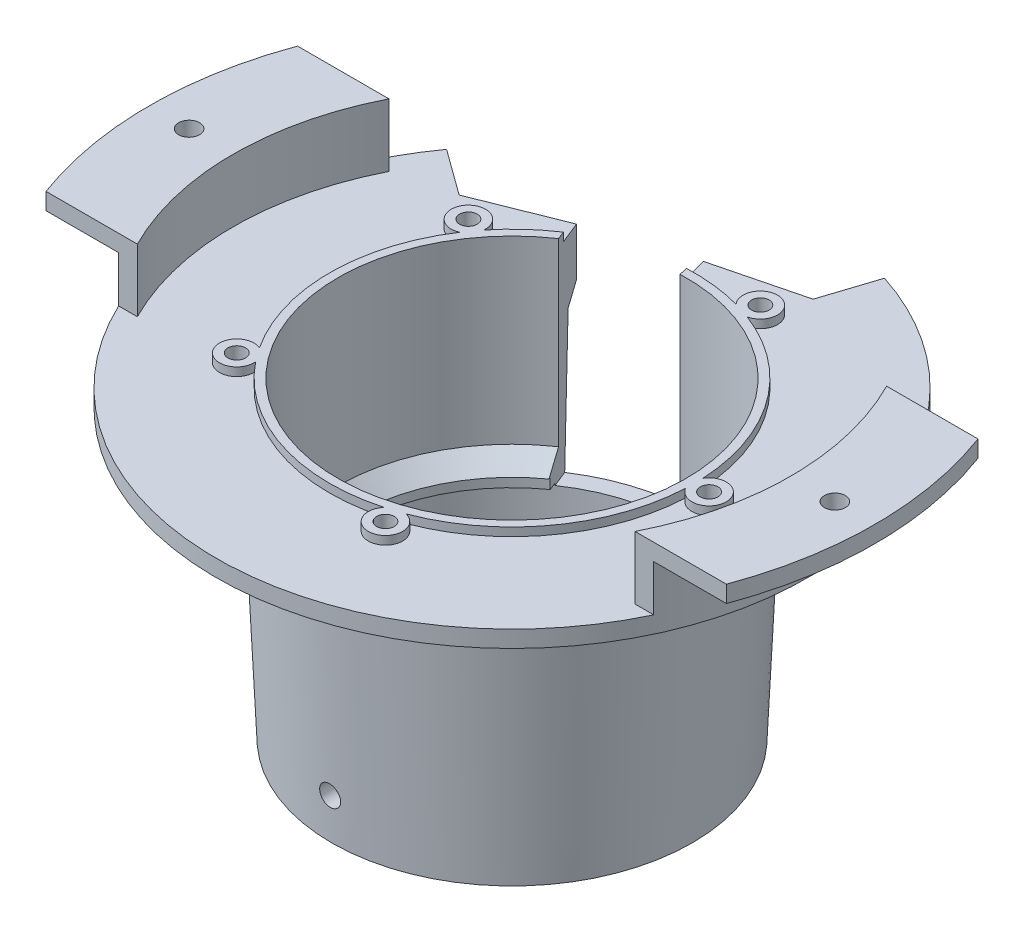
SolidWorks part; units mm, degrees
ref_plane "Front Plane" through (0, 0, 0) normal (0, 0, 1) x (1, 0, 0)
ref_plane "Top Plane" through (0, 0, 0) normal (0, 1, 0) x (1, 0, 0)
ref_plane "Right Plane" through (0, 0, 0) normal (1, 0, 0) x (0, 0, -1)
sketch "Sketch1" plane through (0, 0, 0) normal (0, 0, 1) x (1, 0, 0)
  line L26 (-70.5, -4) -> (-70.5, 11)
  line L27 (-70.5, 11) -> (-86.5, 11)
  line L28 (-86.5, 11) -> (-86.5, 15)
  line L29 (-86.5, 15) -> (-66.5, 15)
  line L30 (-66.5, 15) -> (-66.5, 0)
  line L31 (-66.5, 0) -> (-41.5, 0)
  line L36 (-40, -47.5) -> (-40, -72.5)
  line L37 (-40, -72.5) -> (-43, -72.5)
  line L38 (-37.5, -45) -> (-38, -45)
  line L42 (-41.5, 0) -> (-41.5, -41)
  line L43 (-38, -45) -> (-38, -47.5)
  line L44 (-38, -47.5) -> (-40, -47.5)
  line L45 (-70.5, -4) -> (-56.5, -4)
  line L47 (-45.5, -15) -> (-43, -72.5)
  line L48 (-56.5, -4) -> (-45.5, -15)
  line L49 (-37.5, -45) -> (-41.5, -41)
  dimension "D2" = 45
  dimension "D3" = 2
  dimension "D4" = 41.5
  dimension "D5" = 135
  dimension "D6" = 2.5
  dimension "D7" = 15
  dimension "D8" = 4
  dimension "D9" = 40
  dimension "D10" = 3
  dimension "D11" = 20
  dimension "D12" = 4
  dimension "D13" = 4
  dimension "D14" = 25
  dimension "D15" = 4
  dimension "D16" = 25
  dimension "D17" = 15
  dimension "D18" = 15
  dimension "D19" = 4
ref_axis "Axis1" through (0, -100.5, 0) along (0, 1, 0)
revolve "Revolve1" add sketch "Sketch1" angle 360 about axis through (0, -100.5, 0) along (0, 1, 0)
sketch "Sketch2" plane through (0, 11, 0) normal (0, -1, 0) x (1, 0, 0)
  circle A0 centre (77, 0) radius 2.5
  circle A1 centre (-77, 0) radius 2.5
  dimension "D1" = 5
  dimension "D3" = 77
  dimension "D2" = 77
extrude "Cut-Extrude3" cut sketch "Sketch2" against normal up to surface (4 mm away) up to face at (0, 15, -86.5)
sketch "Sketch3" plane through (0, 15, 0) normal (0, 1, 0) x (1, 0, 0)
  line L0 (-59.3485, -30) -> (-81.1311, -30)
  line L1 (81.1311, -30) -> (59.3485, -30)
  line L5 (81.1311, 30) -> (59.3485, 30)
  line L9 (-59.3485, 30) -> (-81.1311, 30)
  circle A0 centre (0, 0) radius 86.5 construction
  circle A1 centre (-77, 0) radius 2.5 construction
  arc A2 (-81.1311, -30) -> (81.1311, -30) centre (0, 0) ccw
  circle A3 centre (0, 0) radius 66.5 construction
  arc A4 (-59.3485, -30) -> (59.3485, -30) centre (0, 0) ccw
  arc A5 (59.3485, 30) -> (-59.3485, 30) centre (0, 0) ccw
  arc A6 (81.1311, 30) -> (-81.1311, 30) centre (0, 0) ccw
  dimension "D2" = 30
  dimension "D1" = 30
extrude "Cut-Extrude4" cut sketch "Sketch3" against normal up to surface (15 mm away) up to face at (0, 0, -66.5)
sketch "Sketch6" plane through (0, 0, 0) normal (0, 0, 1) x (1, 0, 0)
  line L0 (0, -100.5) -> (0, 20.5) construction
  line L2 (-43, -72.5) -> (43, -72.5) construction
  circle A0 centre (0, -62.5) radius 2.5
  dimension "D1" = 5
  dimension "D2" = 10
extrude "Cut-Extrude6" cut sketch "Sketch6" against normal through all both and the other way through all
sketch "Sketch7" plane through (0, 0, 0) normal (0, 1, 0) x (1, 0, 0)
  circle A0 centre (47, 0) radius 2.1
  dimension "D1" = 4.2
  dimension "D2" = 47
extrude "Cut-Extrude7" cut sketch "Sketch7" against normal up to surface (13.4531 mm away) contours A0
pattern_circular "CirPattern1" count 5 every 72 about axis through (0, 0, 0) along (0, 1, 0) of "Cut-Extrude7"
sketch "Sketch8" plane through (0, 0, 0) normal (0, 1, 0) x (1, 0, 0)
  circle A0 centre (0, 0) radius 41.5 construction
  circle A1 centre (0, 0) radius 41.5
  arc A2 (-33.9458, -27.2017) -> (-17.3102, -39.9075) centre (0, 0) ccw
  circle A3 centre (-38.0238, -27.6259) radius 2.1 construction
  circle A4 centre (14.5238, -44.6997) radius 2.1 construction
  circle A5 centre (47, 0) radius 2.1 construction
  circle A6 centre (14.5238, 44.6997) radius 2.1 construction
  circle A7 centre (-38.0238, 27.6259) radius 2.1 construction
  circle A8 centre (-38.0238, -27.6259) radius 2.1
  circle A9 centre (14.5238, -44.6997) radius 2.1
  circle A10 centre (47, 0) radius 2.1
  circle A11 centre (14.5238, 44.6997) radius 2.1
  circle A12 centre (-38.0238, 27.6259) radius 2.1
  arc A13 (-33.9458, 27.2017) -> (-36.3602, 23.8786) centre (-38.0238, 27.6259) ccw
  arc A14 (15.3805, 40.6902) -> (11.474, 41.9595) centre (14.5238, 44.6997) ccw
  arc A15 (43.4515, -2.0538) -> (43.4515, 2.0538) centre (47, 0) ccw
  arc A16 (11.474, -41.9595) -> (15.3805, -40.6902) centre (14.5238, -44.6997) ccw
  arc A17 (-36.3602, -23.8786) -> (-33.9458, -27.2017) centre (-38.0238, -27.6259) ccw
  arc A18 (15.3805, -40.6902) -> (43.4515, -2.0538) centre (0, 0) ccw
  circle A19 centre (-38.0238, -27.6259) radius 4.1 construction
  circle A20 centre (0, 0) radius 43.5 construction
  circle A21 centre (14.5238, -44.6997) radius 4.1 construction
  arc A22 (43.4515, 2.0538) -> (15.3805, 40.6902) centre (0, 0) ccw
  arc A23 (11.474, 41.9595) -> (-33.9458, 27.2017) centre (0, 0) ccw
  circle A24 centre (47, 0) radius 4.1 construction
  arc A25 (-36.3602, 23.8786) -> (-36.3602, -23.8786) centre (0, 0) ccw
  circle A26 centre (14.5238, 44.6997) radius 4.1 construction
  circle A27 centre (-38.0238, 27.6259) radius 4.1 construction
  arc A33 (-17.3102, -39.9075) -> (11.474, -41.9595) centre (0, 0) ccw
  point P4 (18.6238, -44.6997)
  point P23 (-33.9238, 27.6259)
  point P29 (41.5993, 12.7182)
  point P30 (-33.9238, -27.6259)
  point P39 (51.1, 0)
  point P42 (18.6238, 44.6997)
  point P49 (-16.377, -50.4063)
  point P57 (-8.777, -50.4063)
  dimension "D1" = 2
  dimension "D2" = 2
extrude "Boss-Extrude1" add sketch "Sketch8" along normal blind 2
sketch "Sketch9" plane through (0, 2, 0) normal (0, 1, 0) x (1, 0, 0)
  line L0 (-26.114, 41.5038) -> (-46.114, 33.5038)
  line L1 (-46.114, 33.5038) -> (-57.0357, 41.4389)
  line L2 (-57.0357, 41.4389) -> (-45.8058, 62.9454)
  line L3 (0, 0) -> (-26.114, 80.3707) construction
  line L4 (-45.8058, 62.9454) -> (-23.2656, 71.6041)
  line L5 (0, 0) -> (-38.0238, 27.6259) construction
  line L6 (-26.114, 41.5038) -> (-18.5619, 22.6237)
  line L7 (-18.5619, 22.6237) -> (1.7191, 29.2134)
  line L8 (-3.2687, 48.9267) -> (1.7191, 29.2134)
  line L9 (-3.2687, 48.9267) -> (17.614, 54.2102)
  line L10 (17.614, 54.2102) -> (21.7857, 67.0495)
  line L11 (21.7857, 67.0495) -> (0.0593, 77.8479)
  line L12 (0.0593, 77.8479) -> (-23.2656, 71.6041)
  point P3 (-8.4214, 25.9185)
  point P10 (-15.7151, 48.3662)
  dimension "D1" = 10
  dimension "D2" = 20
  dimension "D3" = 8
extrude "Cut-Extrude8" cut sketch "Sketch9" against normal blind 50 and the other way through all
